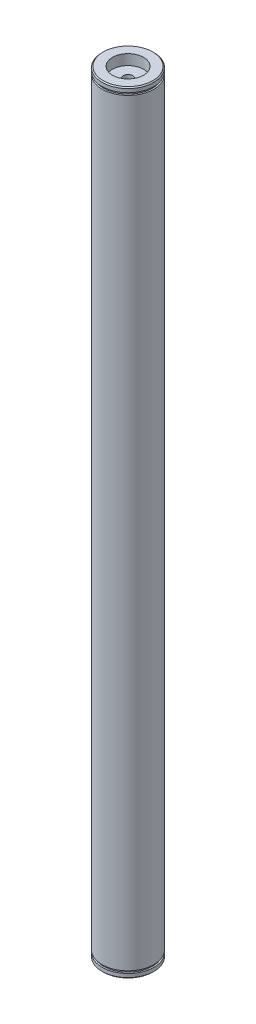
SolidWorks part; units mm, degrees
material "45"
ref_plane "前视基准面" through (0, 0, 0) normal (0, 0, 1) x (1, 0, 0)
ref_plane "上视基准面" through (0, 0, 0) normal (0, 1, 0) x (1, 0, 0)
ref_plane "右视基准面" through (0, 0, 0) normal (1, 0, 0) x (0, 0, -1)
sketch "草图1" plane through (0, 0, 0) normal (0, 1, 0) x (1, 0, 0)
  circle A0 centre (0, 0) radius 25
  dimension "D1" = 50
extrude "凸台-拉伸1" add sketch "草图1" along normal mid plane 746
sketch "草图2" plane through (0, 373, 0) normal (0, 1, 0) x (1, 0, 0)
  circle A0 centre (0, 0) radius 15
  dimension "D1" = 30
extrude "切除-拉伸1" cut sketch "草图2" against normal blind 10
hole_wizard "Ø8.0 (8) 直径孔1" positions "3D草图1" profile "草图4" hole size "Ø8.0" standard "GB"
sketch3d "3D草图1"
  line L0 (0, 373, 0) -> (0, -373, 0) construction
  line L1 (0, 363, 0) -> (0, 373, 0) construction
  point P0 (0, 363, 0)
  point P7 (0, 363, 0)
  point P9 (0, 363, 0)
sketch "草图4" plane through (0, 363, 0) normal (1, 0, 0) x (0, 0, 1)
  line L0 (0, 0) -> (0, 121.4034)
  line L1 (0, 121.4034) -> (4, 119)
  line L2 (4, 119) -> (4, 0)
  line L5 (4, 0) -> (0, 0)
  line L10 (0, 121.4034) -> (-4, 119) construction
  line L11 (0, -6.35) -> (0, 107.95) construction
  dimension "孔直径" = 8
  dimension "孔深度" = 119
  dimension "导头角度" = 118
sketch "草图5" plane through (0, 0, 0) normal (0, 0, 1) x (1, 0, 0)
  line L0 (0, 373) -> (0, -373) construction
  line L1 (25, 373) -> (-25, 373) construction
  line L2 (-25, -373) -> (25, -373) construction
  circle A0 centre (0, 248) radius 3
  dimension "D1" = 6
  dimension "D2" = 125
extrude "切除-拉伸2" cut sketch "草图5" against normal blind 100
hole_wizard "M10x1.0 螺纹孔1" positions "草图6" profile "草图7" tap size "M10x1.0" standard "GB"
sketch "草图6" plane through (0, 363, 0) normal (0, 1, 0) x (1, 0, 0)
  point P0 (0, 0)
sketch "草图7" plane through (0, 363, 0) normal (1, 0, 0) x (0, 0, 1)
  line L0 (0, 0) -> (0, 27.7039)
  line L1 (0, 27.7039) -> (4.5, 25)
  line L2 (4.5, 25) -> (4.5, 0)
  line L5 (4.5, 0) -> (0, 0)
  line L10 (0, 27.7039) -> (-4.5, 25) construction
  line L11 (0, -6.35) -> (0, 107.95) construction
  dimension "螺纹孔钻头直径" = 9
  dimension "螺纹孔钻头深度" = 25
  dimension "导头角度" = 118
cosmetic thread "孔螺蚊线2" parameters "D1"=20, "D2"=10
sketch "草图8" plane through (0, -373, 0) normal (0, -1, 0) x (1, 0, 0)
  circle A0 centre (0, 0) radius 15
  dimension "D1" = 30
extrude "切除-拉伸3" cut sketch "草图8" against normal blind 10
hole_wizard "Ø8.0 (8) 直径孔2" positions "3D草图2" profile "草图9" hole size "Ø8.0" standard "GB"
sketch3d "3D草图2"
  line L0 (0, -363, 0) -> (0, -373, 0) construction
  point P0 (0, -363, 0)
sketch "草图9" plane through (0, -363, 0) normal (1, 0, 0) x (0, 0, -1)
  line L0 (0, 0) -> (0, 121.4034)
  line L1 (0, 121.4034) -> (4, 119)
  line L2 (4, 119) -> (4, 0)
  line L5 (4, 0) -> (0, 0)
  line L10 (0, 121.4034) -> (-4, 119) construction
  line L11 (0, -6.35) -> (0, 107.95) construction
  dimension "孔直径" = 8
  dimension "孔深度" = 119
  dimension "导头角度" = 118
hole_wizard "M10x1.0 螺纹孔2" positions "草图10" profile "草图11" tap size "M10x1.0" standard "GB"
sketch "草图10" plane through (0, -363, 0) normal (0, -1, 0) x (-1, 0, 0)
  point P0 (0, 0)
sketch "草图11" plane through (0, -363, 0) normal (1, 0, 0) x (0, 0, -1)
  line L0 (0, 0) -> (0, 27.7039)
  line L1 (0, 27.7039) -> (4.5, 25)
  line L2 (4.5, 25) -> (4.5, 0)
  line L5 (4.5, 0) -> (0, 0)
  line L10 (0, 27.7039) -> (-4.5, 25) construction
  line L11 (0, -6.35) -> (0, 107.95) construction
  dimension "螺纹孔钻头直径" = 9
  dimension "螺纹孔钻头深度" = 25
  dimension "导头角度" = 118
cosmetic thread "孔螺蚊线1" parameters "D1"=20, "D2"=10
sketch "草图12" plane through (0, 0, 0) normal (0, 0, 1) x (1, 0, 0)
  line L0 (0, 0) -> (0, -373) construction
  line L1 (-25, -373) -> (25, -373) construction
  circle A0 centre (0, -248) radius 3
  dimension "D1" = 6
  dimension "D2" = 125
extrude "切除-拉伸4" cut sketch "草图12" against normal blind 51
chamfer "倒角1" distance 1 angle 45 2 edges at (0, -373, 25) (0, 373, 25)
sketch "草图14" plane through (0, 0, 0) normal (1, 0, 0) x (0, 0, -1)
  line L0 (0, 0) -> (0, 428.7278) construction
  line L1 (0, 0) -> (0, -399.4812) construction
  line L2 (25, 368.5) -> (23.5, 368.5)
  line L3 (25, 251) -> (25, 372) construction
  line L4 (23.5, 368.5) -> (23.5, 366.3)
  line L5 (23.5, 366.3) -> (25, 366.3)
  line L6 (24, 373) -> (-24, 373) construction
  line L7 (25, 368.5) -> (25, 366.3)
  line L8 (25, -368.5) -> (23.5, -368.5)
  line L9 (23.5, -368.5) -> (23.5, -366.3)
  line L10 (23.5, -366.3) -> (25, -366.3)
  line L11 (25, -366.3) -> (25, -368.5)
  line L12 (-24, -373) -> (24, -373) construction
  dimension "D1" = 4.5
  dimension "D2" = 2.2
  dimension "D3" = 1.5
  dimension "D4" = 4.5
  dimension "D5" = 2.2
  dimension "D6" = 1.5
revolve "切除-旋转1" cut sketch "草图14" angle 360 about L0
